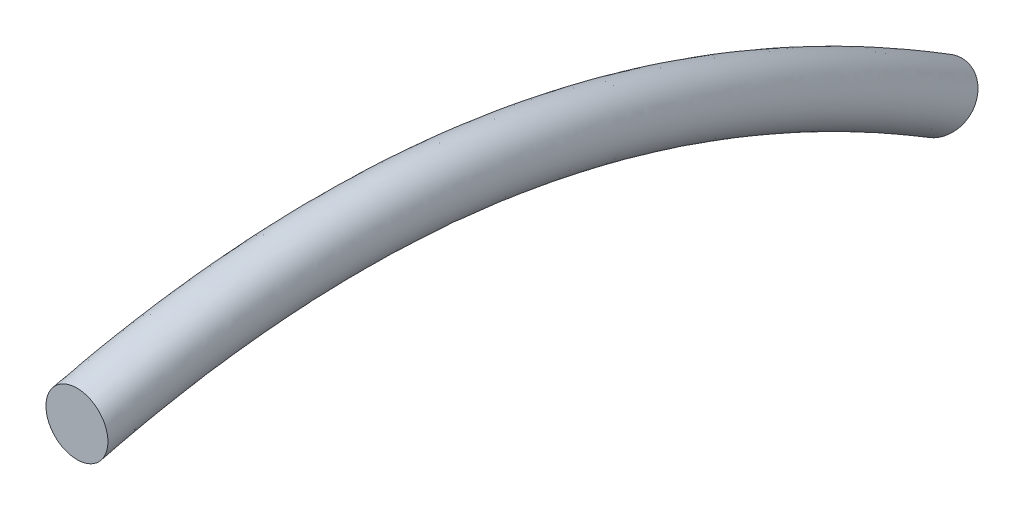
SolidWorks part; units mm, degrees
ref_plane "정면" through (0, 0, 0) normal (0, 0, 1) x (1, 0, 0)
ref_plane "윗면" through (0, 0, 0) normal (0, 1, 0) x (1, 0, 0)
ref_plane "우측면" through (0, 0, 0) normal (1, 0, 0) x (0, 0, -1)
sketch "스케치1" plane through (0, 0, 0) normal (0, 0, 1) x (1, 0, 0)
  circle A0 centre (0, 0) radius 120
sketch "스케치2" plane through (0, 0, 0) normal (1, 0, 0) x (0, 0, -1)
  spline S0 degree 2 poles (0, 0) (1712.9546, 429.5705) (3340.6364, -571.107) knots 0 0 0 1 1 1
  point P2 (0, 0)
  point P4 (203.7399, 35.6869)
  point P5 (0, 0)
  point P7 (2164.2323, -583.8569)
  point P8 (820.2571, 123.961)
  point P9 (3340.6364, -571.107)
sweep "스윕1" add profiles "스케치1" path "스케치2"
